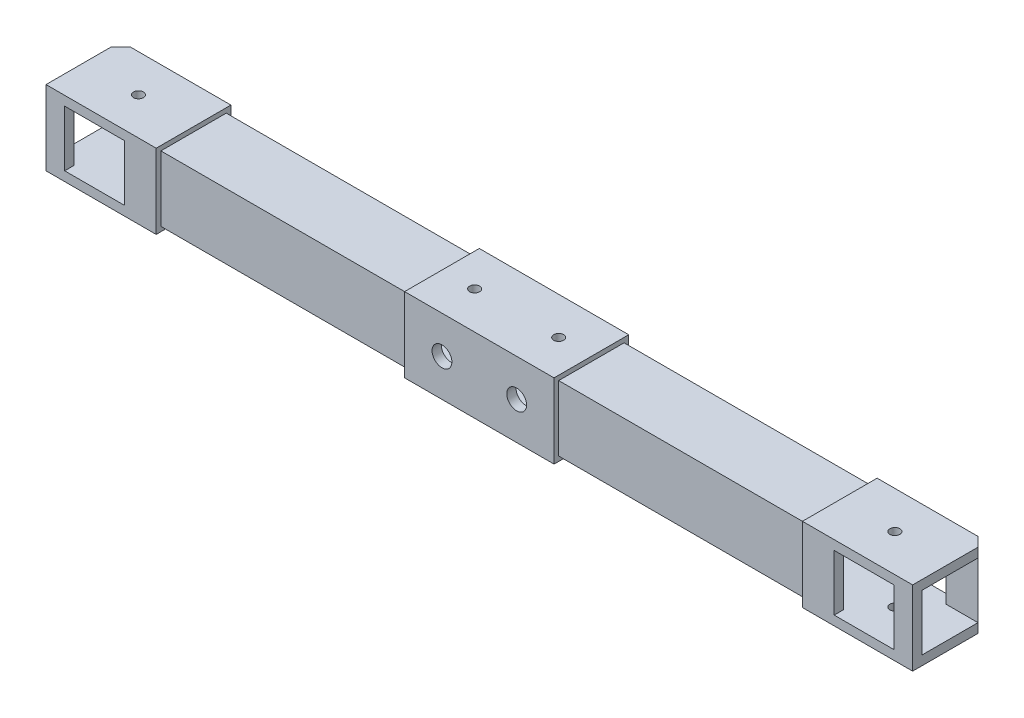
SolidWorks part; units mm, degrees
material "6061-T6 (SS)"
ref_plane "Front" through (0, 0, 0) normal (0, 0, 1) x (1, 0, 0)
ref_plane "Top" through (0, 0, 0) normal (0, 1, 0) x (1, 0, 0)
ref_plane "Right" through (0, 0, 0) normal (1, 0, 0) x (0, 0, -1)
sketch "Sketch1" plane through (0, 0, 0) normal (1, 0, 0) x (0, 0, -1)
  line L0 (-19.05, 19.05) -> (19.05, 19.05)
  line L1 (-25.4, -25.4) -> (25.4, -25.4)
  line L2 (-25.4, -25.4) -> (-25.4, 25.4)
  line L3 (-25.4, 25.4) -> (25.4, 25.4)
  line L4 (25.4, -25.4) -> (25.4, 25.4)
  line L5 (-25.4, -25.4) -> (25.4, 25.4) construction
  line L6 (-25.4, 25.4) -> (25.4, -25.4) construction
  line L7 (19.05, -19.05) -> (19.05, 19.05)
  line L8 (-19.05, -19.05) -> (19.05, -19.05)
  line L9 (-19.05, -19.05) -> (-19.05, 19.05)
  point P0 (0, 0)
  dimension "D1" = 50.8
  dimension "D2" = 50.8
  dimension "D3" = 6.35
extrude "Extrude1" add sketch "Sketch1" along normal mid plane 711.2
hole_wizard "1/2 Clearance Hole1" positions "Sketch5" profile "Sketch4" hole size "1/2" standard "Ansi Inch" end condition through all
sketch "Sketch5" plane through (0, 0, 25.4) normal (0, 0, 1) x (1, 0, 0)
  line L0 (25.4, 0) -> (-25.4, 0) construction
  point P0 (25.4, 0)
  point P1 (-25.4, 0)
  dimension "D1" = 50.8
sketch "Sketch4" plane through (25.4, 0, 25.4) normal (1, 0, 0) x (0, -1, 0)
  line L0 (0, 0) -> (0, 50.8)
  line L1 (0, 50.8) -> (6.7462, 50.8)
  line L2 (6.7462, 50.8) -> (6.7462, 0)
  line L5 (6.7462, 0) -> (0, 0)
  line L11 (0, -6.35) -> (0, 107.95) construction
  dimension "Thru Hole Dia." = 13.4925
  dimension "Thru Hole Depth" = 50.8
sketch "Sketch6" plane through (0, 0, 25.4) normal (0, 0, 1) x (1, 0, 0)
  line L0 (355.6, 19.05) -> (-355.6, 19.05) construction
  line L1 (-281.94, 19.05) -> (-241.3, 19.05)
  line L2 (-281.94, 19.05) -> (-281.94, -19.05)
  line L3 (-281.94, -19.05) -> (-241.3, -19.05)
  line L4 (-241.3, 19.05) -> (-241.3, -19.05)
  line L5 (355.6, -19.05) -> (-355.6, -19.05) construction
  line L6 (0, 25.4) -> (0, -25.4) construction
  line L7 (355.6, 25.4) -> (-355.6, 25.4) construction
  line L8 (355.6, -25.4) -> (-355.6, -25.4) construction
  dimension "D1" = 241.3
  dimension "D2" = 40.64
extrude "Extrude3" cut sketch "Sketch6" against normal up to next
sketch "Sketch7" plane through (0, 0, -25.4) normal (0, 0, -1) x (-1, 0, 0)
  line L0 (-355.6, 19.05) -> (355.6, 19.05) construction
  line L1 (232.41, 19.05) -> (273.05, 19.05)
  line L2 (232.41, 19.05) -> (232.41, -19.05)
  line L3 (232.41, -19.05) -> (273.05, -19.05)
  line L4 (273.05, 19.05) -> (273.05, -19.05)
  line L5 (-355.6, -19.05) -> (355.6, -19.05) construction
  line L7 (281.94, -19.05) -> (241.3, -19.05) construction
  line L9 (241.3, 25.4) -> (241.3, -26.0975) construction
  line L10 (-355.6, 25.4) -> (355.6, 25.4) construction
  line L11 (241.3, -19.05) -> (241.3, 19.05) construction
  dimension "D1" = 31.75
extrude "Extrude4" cut sketch "Sketch7" against normal up to next
sketch "Sketch8" plane through (0, 0, 25.4) normal (0, 0, 1) x (1, 0, 0)
  line L0 (355.6, -25.4) -> (-355.6, -25.4) construction
  line L1 (-355.6, 25.4) -> (-307.34, 25.4)
  line L2 (-355.6, 25.4) -> (-355.6, -25.4)
  line L3 (-355.6, -25.4) -> (-307.34, -25.4)
  line L4 (-307.34, 25.4) -> (-307.34, -25.4)
  line L5 (-281.94, 19.05) -> (-281.94, -19.05) construction
  dimension "D1" = 25.4
extrude "Extrude5" cut sketch "Sketch8" against normal through all
hole_wizard "1/4 Clearance Hole1" positions "Sketch12" profile "Sketch11" hole size "1/4" standard "Ansi Inch" end condition through all
sketch "Sketch12" plane through (0, 25.4, 0) normal (0, 1, 0) x (-1, 0, 0)
  line L0 (257.175, 25.4) -> (257.175, -25.4) construction
  line L1 (-355.6, 25.4) -> (307.34, 25.4) construction
  line L2 (-355.6, -25.4) -> (307.34, -25.4) construction
  line L4 (241.3, 25.4) -> (241.3, -25.4) construction
  point P0 (257.175, 0)
  dimension "D1" = 15.875
sketch "Sketch11" plane through (-257.175, 25.4, 0) normal (1, 0, 0) x (0, 0, 1)
  line L0 (0, 0) -> (0, 50.8)
  line L1 (0, 50.8) -> (3.3782, 50.8)
  line L2 (3.3782, 50.8) -> (3.3782, 0)
  line L5 (3.3782, 0) -> (0, 0)
  line L11 (0, -6.35) -> (0, 107.95) construction
  dimension "Thru Hole Dia." = 6.7564
  dimension "Thru Hole Depth" = 50.8
hole_wizard "1/4 Clearance Hole2" positions "Sketch14" profile "Sketch13" hole size "1/4" standard "Ansi Inch" end condition through all
sketch "Sketch14" plane through (0, 25.4, 0) normal (0, 1, 0) x (-1, 0, 0)
  line L0 (28.575, 25.4) -> (28.575, -25.4) construction
  line L1 (-355.6, 25.4) -> (307.34, 25.4) construction
  line L2 (-355.6, -25.4) -> (307.34, -25.4) construction
  circle A0 centre (257.175, 0) radius 3.3782 construction
  point P0 (28.575, 0)
  dimension "D1" = 228.6
sketch "Sketch13" plane through (-28.575, 25.4, 0) normal (1, 0, 0) x (0, 0, 1)
  line L0 (0, 0) -> (0, 50.8)
  line L1 (0, 50.8) -> (3.3782, 50.8)
  line L2 (3.3782, 50.8) -> (3.3782, 0)
  line L5 (3.3782, 0) -> (0, 0)
  line L11 (0, -6.35) -> (0, 107.95) construction
  dimension "Thru Hole Dia." = 6.7564
  dimension "Thru Hole Depth" = 50.8
sketch "Sketch15" plane through (0, 25.4, 0) normal (0, 1, 0) x (1, 0, 0)
  line L0 (-307.34, 25.4) -> (-288.29, 25.4)
  line L1 (355.6, 25.4) -> (-307.34, 25.4) construction
  line L2 (-288.29, 25.4) -> (-307.34, 6.35)
  line L4 (-307.34, 6.35) -> (-307.34, 25.4)
  dimension "D1" = 19.05
extrude "Extrude6" cut sketch "Sketch15" against normal through all
mirror "Mirror1" about plane through (0, 0, 0) normal (1, 0, 0) of "Extrude3", "Extrude4", "Extrude5", "1/4 Clearance Hole1", "1/4 Clearance Hole2", "Extrude6"
sketch "Sketch17" plane through (0, -25.4, 0) normal (0, -1, 0) x (1, 0, 0)
  circle A0 centre (-28.575, 0) radius 9.525
  circle A1 centre (28.575, 0) radius 9.525
  dimension "D1" = 19.05
extrude "Extrude8" cut sketch "Sketch17" against normal up to next
sketch "Sketch18" plane through (0, 25.4, 0) normal (0, 1, 0) x (1, 0, 0)
  line L0 (307.34, -25.4) -> (-307.34, -25.4) construction
  line L1 (-294.64, -25.4) -> (-307.34, -25.4)
  line L2 (-294.64, -25.4) -> (-294.64, 25.4)
  line L3 (-294.64, 25.4) -> (-307.34, 25.4)
  line L4 (-307.34, -25.4) -> (-307.34, 25.4)
  line L5 (-307.34, 6.35) -> (-307.34, -25.4) construction
  line L6 (-281.94, -25.4) -> (-281.94, 25.4) construction
  line L7 (288.29, 25.4) -> (-288.29, 25.4) construction
  dimension "D1" = 12.7
extrude "Extrude9" cut sketch "Sketch18" against normal through all
mirror "Mirror2" about plane through (0, 0, 0) normal (1, 0, 0) of "Extrude9"
sketch "Sketch19" plane through (0, 0, -25.4) normal (0, 0, -1) x (-1, 0, 0)
  line L0 (-288.29, 25.4) -> (288.29, 25.4) construction
  line L1 (-219.71, 25.4) -> (-50.8, 25.4)
  line L2 (-219.71, 25.4) -> (-219.71, -25.4)
  line L3 (-219.71, -25.4) -> (-50.8, -25.4)
  line L4 (-50.8, 25.4) -> (-50.8, -25.4)
  line L5 (-288.29, -25.4) -> (288.29, -25.4) construction
  line L6 (-232.41, 19.05) -> (-232.41, -19.05) construction
  line L7 (0, 0) -> (0, 25.4) construction
  dimension "D1" = 12.7
  dimension "D2" = 50.8
extrude "Extrude10" cut sketch "Sketch19" against normal blind 3.175
mirror "Mirror3" about plane through (0, 0, 0) normal (0, 0, 1) of "Extrude10"
sketch "Sketch20" plane through (0, -25.4, 0) normal (0, -1, 0) x (1, 0, 0)
  line L1 (50.8, 22.225) -> (219.71, 22.225)
  line L2 (50.8, 22.225) -> (50.8, -22.225)
  line L3 (50.8, -22.225) -> (219.71, -22.225)
  line L4 (219.71, 22.225) -> (219.71, -22.225)
extrude "Extrude11" cut sketch "Sketch20" against normal blind 3.175
mirror "Mirror4" about plane through (0, 0, 0) normal (0, 1, 0) of "Extrude11"
mirror "Mirror5" about plane through (0, 0, 0) normal (1, 0, 0) of "Mirror4", "Extrude11", "Mirror3", "Extrude10"
